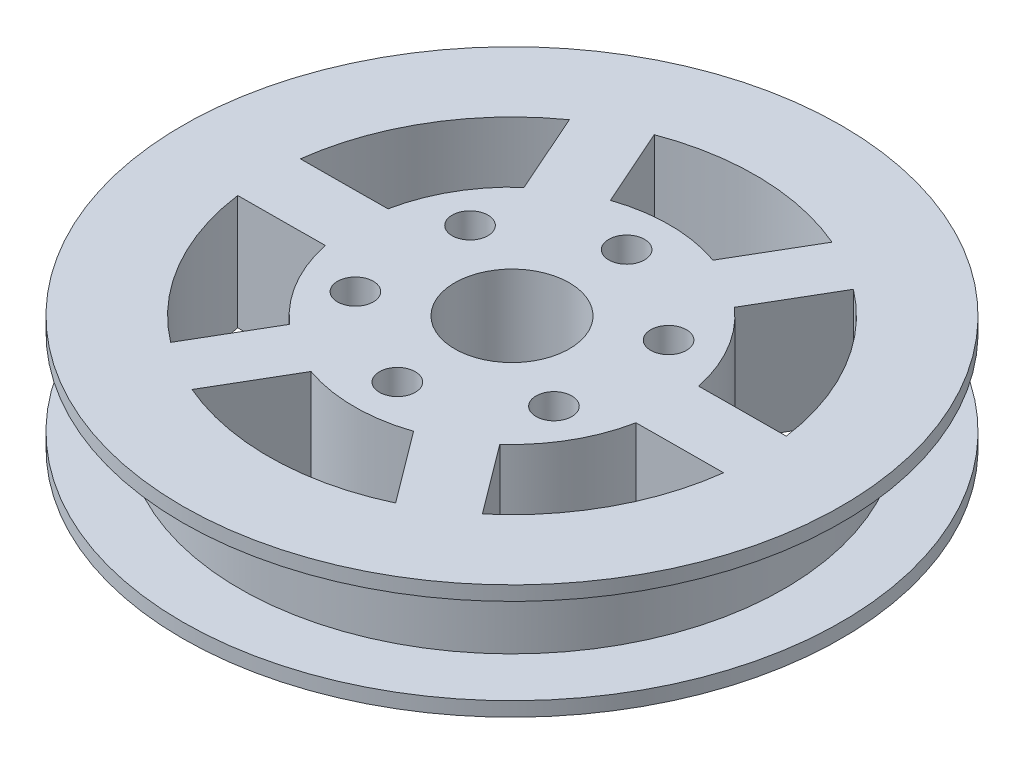
SolidWorks part; units mm, degrees
material "2024 Alloy"
ref_plane "Front Plane" through (0, 0, 0) normal (0, 0, 1) x (1, 0, 0)
ref_plane "Top Plane" through (0, 0, 0) normal (0, 1, 0) x (1, 0, 0)
ref_plane "Right Plane" through (0, 0, 0) normal (1, 0, 0) x (0, 0, -1)
sketch "Sketch2" plane through (0, 0, 0) normal (0, 1, 0) x (1, 0, 0)
  circle A0 centre (0, 0) radius 60.325
  circle A1 centre (0, 0) radius 25.4
  circle A2 centre (0, 25.4) radius 3.9688
  circle A3 centre (21.997, 12.7) radius 3.9688
  circle A4 centre (21.997, -12.7) radius 3.9688
  circle A5 centre (0, -25.4) radius 3.9688
  circle A6 centre (-21.997, -12.7) radius 3.9688
  circle A7 centre (-21.997, 12.7) radius 3.9688
  circle A8 centre (0, 0) radius 12.7
  point P19 (0, 0)
  dimension "D2" = 120.65
  dimension "D3" = 50.8
  dimension "D4" = 7.9375
  dimension "D5" = 25.4
  dimension "D1" = 6
extrude "Boss-Extrude1" add sketch "Sketch2" along normal blind 19.05 contours A0 A7 A1 A2 A3 A4 A5 A6 | A7 A1 A6 A5 A4 A3 A2
sketch "Sketch3" plane through (0, 19.05, 0) normal (0, 1, 0) x (1, 0, 0)
  circle A0 centre (0, 25.4) radius 3.9688 construction
  circle A1 centre (21.997, 12.7) radius 3.9688 construction
  circle A2 centre (21.997, -12.7) radius 3.9688 construction
  circle A3 centre (0, -25.4) radius 3.9688 construction
  circle A4 centre (-21.997, -12.7) radius 3.9688 construction
  circle A5 centre (0, 0) radius 12.7 construction
  circle A6 centre (-21.997, 12.7) radius 3.9688 construction
  circle A7 centre (0, 25.4) radius 3.9688
  circle A8 centre (21.997, 12.7) radius 3.9688
  circle A9 centre (21.997, -12.7) radius 3.9688
  circle A10 centre (0, -25.4) radius 3.9688
  circle A11 centre (-21.997, -12.7) radius 3.9688
  circle A12 centre (0, 0) radius 12.7
  circle A13 centre (-21.997, 12.7) radius 3.9688
  circle A14 centre (0, 0) radius 73.025
  dimension "D1" = 146.05
extrude "Boss-Extrude2" add sketch "Sketch3" along normal blind 3.175
sketch "Sketch4" plane through (0, 0, 0) normal (0, -1, 0) x (1, 0, 0)
  circle A0 centre (0, 0) radius 12.7 construction
  circle A1 centre (-21.997, -12.7) radius 3.9688 construction
  circle A2 centre (0, -25.4) radius 3.9688 construction
  circle A3 centre (21.997, -12.7) radius 3.9688 construction
  circle A4 centre (21.997, 12.7) radius 3.9688 construction
  circle A5 centre (0, 25.4) radius 3.9688 construction
  circle A6 centre (-21.997, 12.7) radius 3.9688 construction
  circle A7 centre (0, 0) radius 12.7
  circle A8 centre (-21.997, -12.7) radius 3.9688
  circle A9 centre (0, -25.4) radius 3.9688
  circle A10 centre (21.997, -12.7) radius 3.9688
  circle A11 centre (21.997, 12.7) radius 3.9688
  circle A12 centre (0, 25.4) radius 3.9688
  circle A13 centre (-21.997, 12.7) radius 3.9688
  circle A14 centre (0, 0) radius 73.025 construction
  circle A15 centre (0, 0) radius 73.025
extrude "Boss-Extrude3" add sketch "Sketch4" along normal blind 3.175
sketch "Sketch9" plane through (0, 0, 0) normal (0, 1, 0) x (1, 0, 0)
  line L0 (-21.3143, -49.5883) -> (-11.5918, -32.9452)
  line L1 (-31.2839, 43.9843) -> (-23.3122, 26.0057)
  line L2 (-53.4791, -7.2996) -> (-34.1777, -7.1861)
  line L3 (-32.7272, -42.9212) -> (-23.0047, -26.2781)
  line L4 (-18.9967, 50.5215) -> (-11.2551, 33.0617)
  line L5 (-53.5613, 6.6701) -> (-34.2599, 6.7836)
  line L6 (11.5918, 32.9452) -> (21.3143, 49.5883)
  line L7 (23.0047, 26.2781) -> (32.7272, 42.9212)
  line L8 (34.1777, 7.1861) -> (53.4791, 7.2996)
  line L9 (34.2599, -6.7836) -> (53.5613, -6.6701)
  line L10 (23.3122, -26.0057) -> (34.7428, -41.3067)
  line L11 (11.2551, -33.0617) -> (23.0254, -48.8173)
  circle A0 centre (0, 0) radius 34.925
  circle A1 centre (0, 0) radius 53.975
  circle A2 centre (0, 0) radius 53.975
  circle A3 centre (0, 0) radius 34.925
  point P8 (0, 0)
extrude "Cut-Extrude3" cut sketch "Sketch9" against normal through all both and the other way through all contours L2 A1 L3 A0 | L1 A1 L5 A0 | L6 A1 L4 A0 | L8 A1 L7 A0 | L10 A1 L9 A0 | L0 A1 L11 A0
